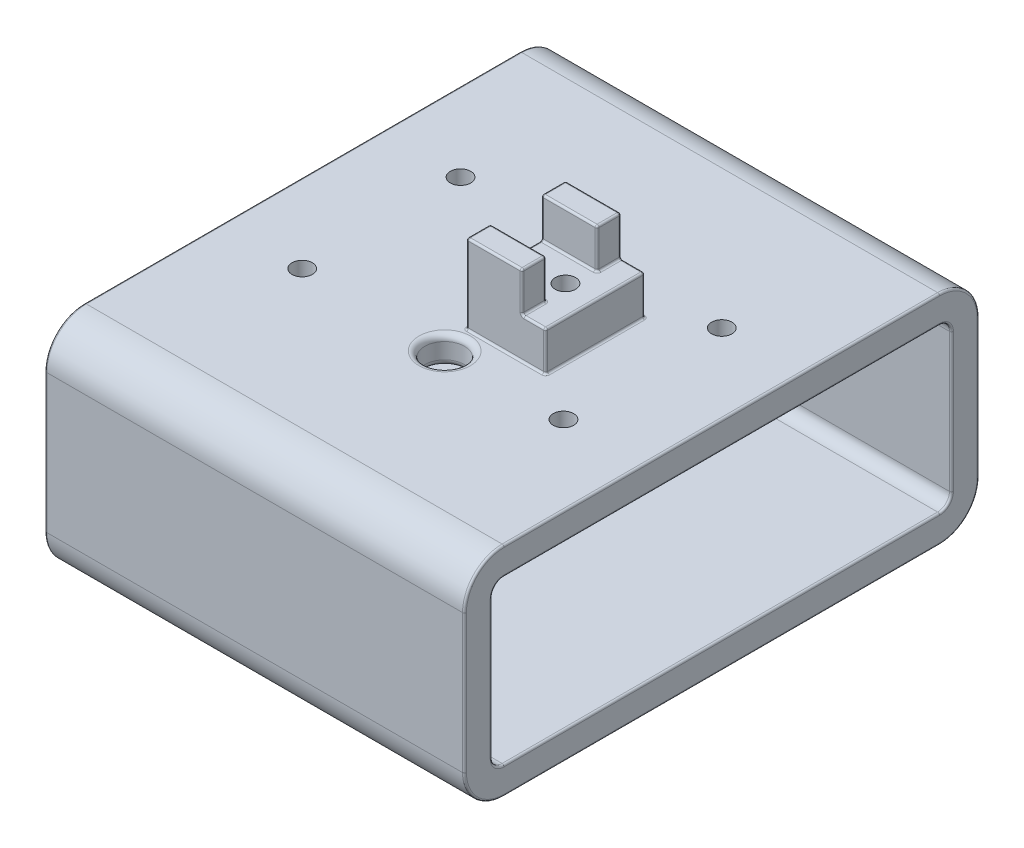
SolidWorks part; units mm, degrees
ref_plane "Front Plane" through (0, 0, 0) normal (0, 0, 1) x (1, 0, 0)
ref_plane "Top Plane" through (0, 0, 0) normal (0, 1, 0) x (1, 0, 0)
ref_plane "Right Plane" through (0, 0, 0) normal (1, 0, 0) x (0, 0, -1)
sketch "Sketch1" plane through (0, 0, 0) normal (1, 0, 0) x (0, 0, -1)
  line L1 (-10, 0) -> (-120, 0)
  line L2 (0, -10) -> (0, -45)
  line L3 (-10, -55) -> (-120, -55)
  line L4 (-130, -10) -> (-130, -45)
  arc A0 (-10, 0) -> (0, -10) centre (-10, -10) cw
  arc A1 (0, -45) -> (-10, -55) centre (-10, -45) cw
  arc A2 (-120, -55) -> (-130, -45) centre (-120, -45) cw
  arc A3 (-120, 0) -> (-130, -10) centre (-120, -10) ccw
  point P7 (0, 0)
  point P10 (0, -55)
  point P15 (-130, 0)
  dimension "D3" = 10
  dimension "D1" = 130
  dimension "D2" = 55
extrude "Boss-Extrude1" add sketch "Sketch1" along normal blind 106
shell "Shell1" thickness 7
sketch "Sketch2" plane through (0, 0, 0) normal (0, 1, 0) x (1, 0, 0)
  line L0 (0, -10) -> (0, -120) construction
  line L1 (74, -77.5) -> (54, -77.5)
  line L2 (74, -77.5) -> (74, -52.5)
  line L3 (74, -52.5) -> (54, -52.5)
  line L4 (54, -77.5) -> (54, -52.5)
  point P6 (0, -65)
  point P7 (74, -65)
  dimension "D1" = 25
  dimension "D2" = 20
  dimension "D3" = 74
extrude "Boss-Extrude2" add sketch "Sketch2" along normal blind 10
sketch "Sketch3" plane through (0, 10, 0) normal (0, 1, 0) x (1, 0, 0)
  line L0 (74, -52.5) -> (54, -52.5) construction
  line L7 (54, -52.5) -> (54, -77.5) construction
  line L8 (54, -71.45) -> (68.0413, -71.45)
  line L9 (54, -71.45) -> (54, -77.5)
  line L10 (54, -77.5) -> (68.0413, -77.5)
  line L11 (68.0413, -71.45) -> (68.0413, -77.5)
  line L12 (54, -77.5) -> (74, -77.5) construction
  line L14 (54, -58.55) -> (68.0413, -58.55)
  line L15 (54, -58.55) -> (54, -52.5)
  line L16 (54, -52.5) -> (68.0413, -52.5)
  line L17 (68.0413, -58.55) -> (68.0413, -52.5)
  dimension "D1" = 12.9
  dimension "D2" = 14.0413
extrude "Boss-Extrude3" add sketch "Sketch3" along normal blind 10
sketch "Sketch4" plane through (0, 10, 0) normal (0, 1, 0) x (1, 0, 0)
  line L0 (74, -77.5) -> (74, -52.5) construction
  circle A0 centre (66.5, -65) radius 2.575
  point P5 (74, -65)
  dimension "D1" = 5.15
  dimension "D2" = 7.5
extrude "Cut-Extrude1" cut sketch "Sketch4" against normal up to surface (17 mm away) up to face at (56.5, -7, 65)
sketch "Sketch5" plane through (0, 0, 0) normal (0, 1, 0) x (1, 0, 0)
  line L0 (0, -10) -> (0, -120) construction
  line L1 (0, -65) -> (26.0028, -65) construction
  line L2 (53, -130) -> (53, -79.5682) construction
  line L3 (106, -130) -> (0, -130) construction
  circle A0 centre (20, -85) radius 2.575
  circle A1 centre (20, -45) radius 2.575
  circle A2 centre (86, -45) radius 2.575
  circle A3 centre (86, -85) radius 2.575
  dimension "D1" = 5.15
  dimension "D2" = 20
  dimension "D3" = 20
extrude "Cut-Extrude2" cut sketch "Sketch5" against normal up to surface (7 mm away) up to face at (66.5, -7, 62.425)
fillet "Fillet1" radius 0.5 30 edges at (61.0207, 10, 71.45) (68.0413, 10, 55.525) (68.0413, 15, 58.55) (61.0207, 10, 58.55) (54, 10, 77.5) (68.0413, 20, 55.525) (54, 20, 55.525) (54, 10, 65) (54, 20, 74.475) (61.0207, 20, 71.45) (54, 15, 71.45) (61.0207, 20, 77.5) (68.0413, 15, 77.5) (68.0413, 20, 74.475) (68.0413, 15, 71.45) (68.0413, 10, 74.475) (61.0207, 20, 58.55) (61.0207, 20, 52.5) (54, 10, 52.5) (54, 0, 65) (54, 15, 58.55) (68.0413, 15, 52.5) (71.0207, 10, 52.5) (74, 5, 52.5) (74, 5, 77.5) (74, 10, 65) (71.0207, 10, 77.5) (64, 0, 52.5) (74, 0, 65) (64, 0, 77.5)
sketch "Sketch6" plane through (0, 0, 0) normal (0, 0, -1) x (-1, 0, 0)
  line L0 (-106, 0) -> (0, 0) construction
  line L1 (-66, -20) -> (-51.4, -20)
  line L2 (-66, -20) -> (-66, -28.42)
  line L3 (-66, -28.42) -> (-51.4, -28.42)
  line L4 (-51.4, -20) -> (-51.4, -28.42)
  line L5 (-106, -45) -> (-106, -10) construction
  dimension "D1" = 14.6
  dimension "D2" = 8.42
  dimension "D3" = 20
  dimension "D4" = 40
extrude "Cut-Extrude3" cut sketch "Sketch6" against normal up to surface (7 mm away) up to face at (56.5, -27.5, 7)
sketch "Sketch7" plane through (0, 0, 0) normal (0, 1, 0) x (1, 0, 0)
  line L0 (106, -10) -> (106, -120) construction
  line L1 (106, -130) -> (0, -130) construction
  circle A0 centre (56, -85) radius 5
  dimension "D1" = 10
  dimension "D2" = 50
  dimension "D3" = 45
extrude "Cut-Extrude4" cut sketch "Sketch7" against normal up to surface (7 mm away) up to face at (86, -7, 82.425)
sketch "Sketch8" plane through (0, 0, 0) normal (-1, 0, 0) x (0, 0, 1)
  line L0 (10, 0) -> (120, 0) construction
  circle A0 centre (65, -15) radius 6
  point P5 (65, 0)
  dimension "D1" = 12
  dimension "D2" = 15
extrude "Cut-Extrude5" cut sketch "Sketch8" against normal up to surface (7 mm away) up to face at (7, -27.5, 65)
fillet "Fillet2" radius 0.5 24 edges at (106, -55, 65) (106, -27.5, 130) (0, -55, 65) (0, -27.5, 130) (0, 0, 65) (0, -27.5, 0) (106, -27.5, 0) (106, -7, 65) (106, 0, 65) (0, -52.0711, 2.9289) (0, -52.0711, 127.0711) (0, -2.9289, 127.0711) (0, -2.9289, 2.9289) (106, -7.8787, 7.8787) (106, -27.5, 7) (106, -47.1213, 7.8787) (106, -48, 65) (106, -47.1213, 122.1213) (106, -27.5, 123) (106, -7.8787, 122.1213) (106, -2.9289, 2.9289) (106, -52.0711, 2.9289) (106, -52.0711, 127.0711) (106, -2.9289, 127.0711)
fillet "Fillet4" radius 1.5 4 edges at (56, -7, 80) (56, 0, 90) (7, -15, 71) (0, -15, 71)
